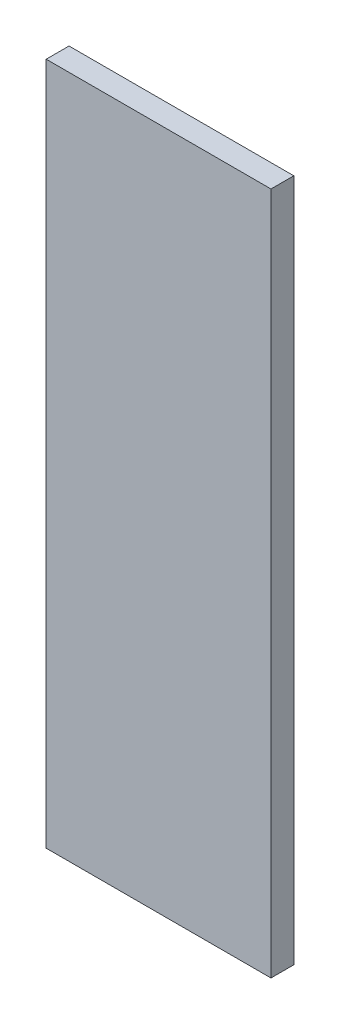
SolidWorks part; units mm, degrees
ref_plane "Front Plane" through (0, 0, 0) normal (0, 0, 1) x (1, 0, 0)
ref_plane "Top Plane" through (0, 0, 0) normal (0, 1, 0) x (1, 0, 0)
ref_plane "Right Plane" through (0, 0, 0) normal (1, 0, 0) x (0, 0, -1)
sketch "Sketch1" plane through (0, 0, 0) normal (0, 0, 1) x (1, 0, 0)
  line L1 (-62.5, -190) -> (62.5, -190)
  line L2 (-62.5, -190) -> (-62.5, 190)
  line L3 (-62.5, 190) -> (62.5, 190)
  line L4 (62.5, -190) -> (62.5, 190)
  line L5 (-62.5, -190) -> (62.5, 190) construction
  line L6 (-62.5, 190) -> (62.5, -190) construction
  point P0 (0, 0)
  dimension "D1" = 125
  dimension "D2" = 380
extrude "Boss-Extrude1" add sketch "Sketch1" along normal mid plane 12.7
